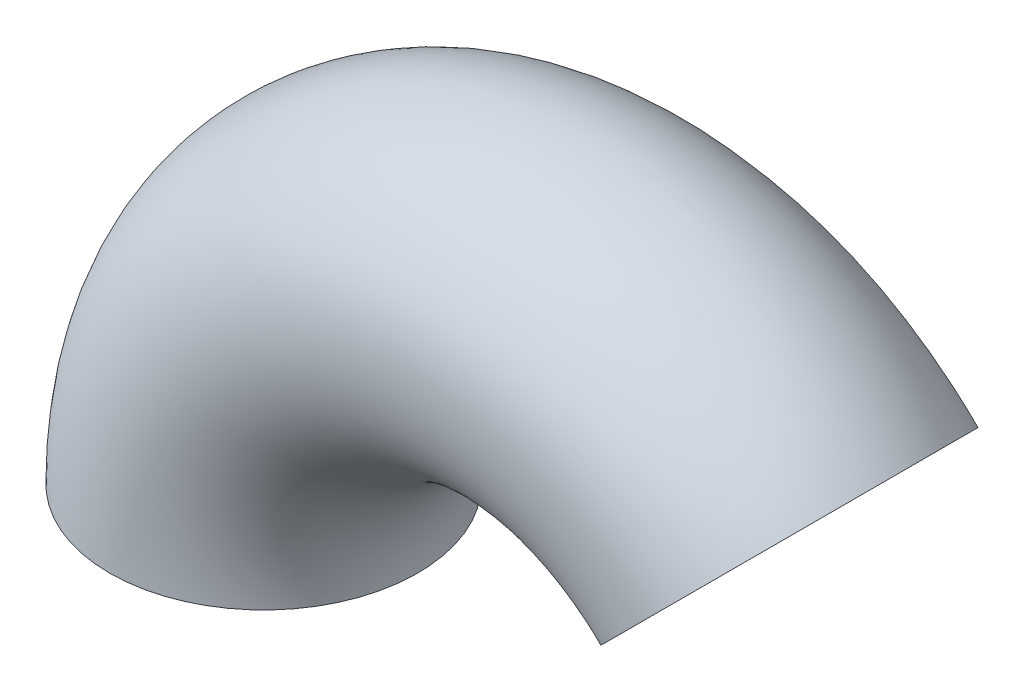
SolidWorks part; units mm, degrees
ref_plane "Front Plane" through (0, 0, 0) normal (0, 0, 1) x (1, 0, 0)
ref_plane "Top Plane" through (0, 0, 0) normal (0, 1, 0) x (1, 0, 0)
ref_plane "Right Plane" through (0, 0, 0) normal (1, 0, 0) x (0, 0, -1)
sketch "Sketch1" plane through (0, 0, 0) normal (0, 0, 1) x (1, 0, 0)
  arc A1 (0, 0) -> (81.0842, 33.5862) centre (47.498, 0) cw
  dimension "D1" = 47.498
sketch "Sketch2" plane through (0, 0, 0) normal (0, 1, 0) x (1, 0, 0)
  circle A0 centre (0, 0) radius 23.749
  dimension "D1" = 47.498
sweep "Sweep3" add profiles "Sketch2" path "Sketch1"
shell "Shell1" thickness 2.54
equation "\"FoamCore\" = \".2\""
equation "\"MDF\" = \".2\""
equation "\"GMaterial\"= \".2\""
equation "\"PVCMountDiameter\" = \"0.5in\""
equation "\"PVCMountDistanceToEdge\" = \"0.5\""
equation "\"PVCThickness\" = \"0.13in\""
equation "\"BaseWidth\" = \"8in\""
equation "\"BaseLength\" = \"10in\""
equation "\"BallDiameter\" = \"1.57in\""
equation "\"BaseGap\" = \"4in\""
equation "\"FunnelTopDiameter\" = \"8in\""
equation "\"FunnelTopDepth\" = \"1.5in\""
equation "\"BallGap\" = \"0.1in\""
equation "\"FunnelLength\" = 6in"
equation "\"FunnelMaterial\" = 0.1in"
equation "\"FunnelLowerDiameter\" = \"PVCDiameter\" + \"PVCThickness\"*2"
equation "\"FunnelDepth\" = 1.5in"
equation "\"AmmoFeederLength\" = 1in + 76mm"
equation "\"AmmoFeederCutoffLength\" = \"MovingWheelDiameter\""
equation "\"D1@Sketch2\"=\"FunnelLowerDiameter\""
equation "\"D3@Sweep\"= \"FunnelLowerDiameter\""
equation "\"D1@Sketch1\"=\"FunnelLowerDiameter\""
equation "\"D1@Shell1\"=\"FunnelMaterial\""
equation "\"FunnelBendLength\" = 2*pi*\"FunnelLowerDiameter\"/2*135"
equation "\"WheelThickness\" = 0.5in"
equation "\"LauncherWheelDiameter\" = 60mm"
equation "\"MotorFrontLength\" = 0.95in"
equation "\"MotorBodyTotalLength\" = 2.03in"
equation "\"MotorFrontDiameter\" = 1.5in"
equation "\"MotorLowerDriveshaftDiameter\" = 0.46in"
equation "\"MotorLowerDriveshaftThickness\" = 0.25in"
equation "\"MotorFullDriveshaftLength\" = 0.78in"
equation "\"MotorDriveshaftDiameter\" = 0.23in"
equation "\"MotorDriveshaftFlatThickness\" = 0.2in"
equation "\"MotorRearDiameter\" = 31.9mm"
equation "\"MotorDriveshaftBottomToTop\" = 31.1mm"
equation "\"MotorFlatDriveshaftLength\" = 11.7mm"
equation "\"MotorDistanceBetweenLowerandTopHoles\" = 0.5in"
equation "\"MotorMountsDistanceFromEdge\" = 0.06in"
equation "\"MotorScrewMountDiameter\" = 0.1in"
equation "\"MotorScrewMountDepth\" = 0.13in"
equation "\"HBRidgeScrewHoleDeep\" = 0.18in"
equation "\"MotorMountWidth\" = \"1.61in\""
